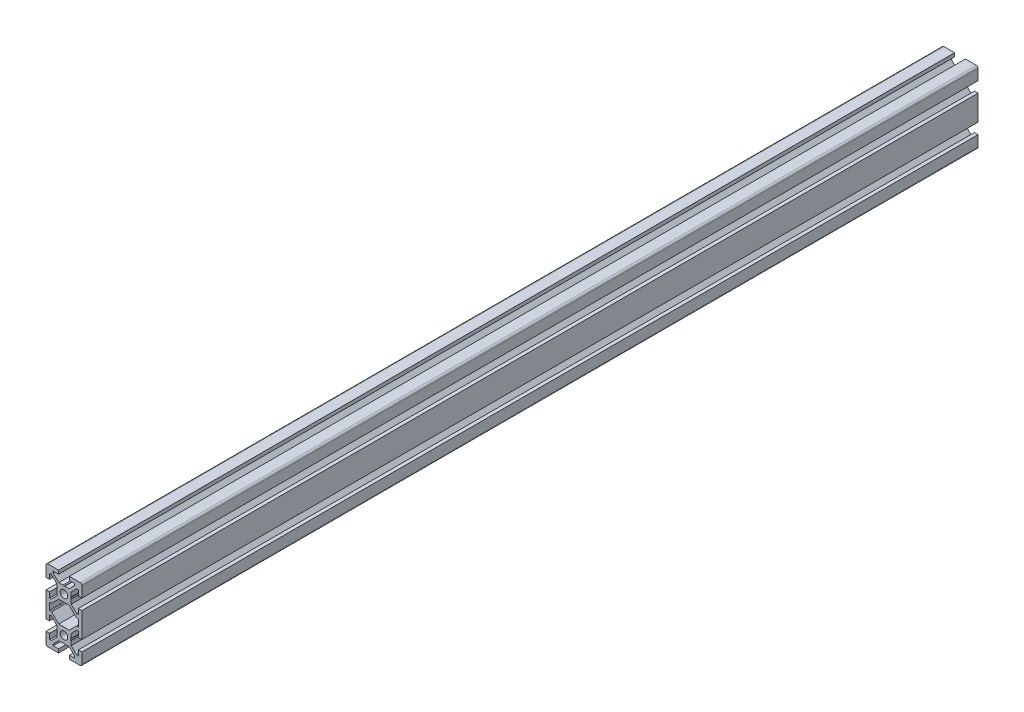
SolidWorks part; units mm, degrees
material "6063-T5"
ref_plane "Front Plane" through (0, 0, 0) normal (0, 0, 1) x (1, 0, 0)
ref_plane "Top Plane" through (0, 0, 0) normal (0, 1, 0) x (1, 0, 0)
ref_plane "Right Plane" through (0, 0, 0) normal (1, 0, 0) x (0, 0, -1)
ref_plane "Plane1" through (0, 0, -50) normal (0, 0, -1) x (-1, 0, 0)
sketch "Sketch1" plane through (0, 0, -50) normal (0, 0, -1) x (-1, 0, 0)
  line L0 (8, 1.7) -> (8, -1.7)
  line L1 (7.7, -2) -> (7.0636, -2)
  line L2 (6.8515, -2.0879) -> (2.9393, -6)
  line L3 (2.9393, -6) -> (-2.9393, -6)
  line L4 (-2.9393, -6) -> (-6.8515, -2.0879)
  line L5 (-7.0636, -2) -> (-7.7, -2)
  line L6 (-8, -1.7) -> (-8, 1.7)
  line L7 (-7.7, 2) -> (-7.0636, 2)
  line L8 (-6.8515, 2.0879) -> (-2.9393, 6)
  line L9 (-2.9393, 6) -> (2.9393, 6)
  line L10 (2.9393, 6) -> (6.8515, 2.0879)
  line L11 (7.0636, 2) -> (7.7, 2)
  line L12 (10, -7) -> (10, 7)
  line L13 (10, 7) -> (8, 7)
  line L14 (8, 7) -> (8, 4)
  line L15 (8, 4) -> (7.0607, 4)
  line L16 (7.0607, 4) -> (4, 7.0607)
  line L17 (4, 7.0607) -> (4, 9.4804)
  line L18 (4, 9.4804) -> (3.7, 10)
  line L19 (3.7, 10) -> (4, 10.5196)
  line L20 (4, 10.5196) -> (4, 12.9393)
  line L21 (4, 12.9393) -> (7.0607, 16)
  line L22 (7.0607, 16) -> (8, 16)
  line L23 (8, 16) -> (8, 13)
  line L24 (8, 13) -> (10, 13)
  line L25 (10, 13) -> (10, 19)
  line L26 (9, 20) -> (3, 20)
  line L27 (3, 20) -> (3, 18)
  line L28 (3, 18) -> (6, 18)
  line L29 (6, 18) -> (6, 17.0607)
  line L30 (6, 17.0607) -> (2.9393, 14)
  line L31 (2.9393, 14) -> (0.5196, 14)
  line L32 (0.5196, 14) -> (0, 13.7)
  line L33 (0, 13.7) -> (-0.5196, 14)
  line L34 (-0.5196, 14) -> (-2.9393, 14)
  line L35 (-2.9393, 14) -> (-6, 17.0607)
  line L36 (-6, 17.0607) -> (-6, 18)
  line L37 (-6, 18) -> (-3, 18)
  line L38 (-3, 18) -> (-3, 20)
  line L39 (-3, 20) -> (-9, 20)
  line L40 (-10, 19) -> (-10, 13)
  line L41 (-10, 13) -> (-8, 13)
  line L42 (-8, 13) -> (-8, 16)
  line L43 (-8, 16) -> (-7.0607, 16)
  line L44 (-7.0607, 16) -> (-4, 12.9393)
  line L45 (-4, 12.9393) -> (-4, 10.5196)
  line L46 (-4, 10.5196) -> (-3.7, 10)
  line L47 (-3.7, 10) -> (-4, 9.4804)
  line L48 (-4, 9.4804) -> (-4, 7.0607)
  line L49 (-4, 7.0607) -> (-7.0607, 4)
  line L50 (-7.0607, 4) -> (-8, 4)
  line L51 (-8, 4) -> (-8, 7)
  line L52 (-8, 7) -> (-10, 7)
  line L53 (-10, 7) -> (-10, -7)
  line L54 (-10, -7) -> (-8, -7)
  line L55 (-8, -7) -> (-8, -4)
  line L56 (-8, -4) -> (-7.0607, -4)
  line L57 (-7.0607, -4) -> (-4, -7.0607)
  line L58 (-4, -7.0607) -> (-4, -9.4804)
  line L59 (-4, -9.4804) -> (-3.7, -10)
  line L60 (-3.7, -10) -> (-4, -10.5196)
  line L61 (-4, -10.5196) -> (-4, -12.9393)
  line L62 (-4, -12.9393) -> (-7.0607, -16)
  line L63 (-7.0607, -16) -> (-8, -16)
  line L64 (-8, -16) -> (-8, -13)
  line L65 (-8, -13) -> (-10, -13)
  line L66 (-10, -13) -> (-10, -19)
  line L67 (-9, -20) -> (-3, -20)
  line L68 (-3, -20) -> (-3, -18)
  line L69 (-3, -18) -> (-6, -18)
  line L70 (-6, -18) -> (-6, -17.0607)
  line L71 (-6, -17.0607) -> (-2.9393, -14)
  line L72 (-2.9393, -14) -> (-0.5196, -14)
  line L73 (-0.5196, -14) -> (0, -13.7)
  line L74 (0, -13.7) -> (0.5196, -14)
  line L75 (0.5196, -14) -> (2.9393, -14)
  line L76 (2.9393, -14) -> (6, -17.0607)
  line L77 (6, -17.0607) -> (6, -18)
  line L78 (6, -18) -> (3, -18)
  line L79 (3, -18) -> (3, -20)
  line L80 (3, -20) -> (9, -20)
  line L81 (10, -19) -> (10, -13)
  line L82 (10, -13) -> (8, -13)
  line L83 (8, -13) -> (8, -16)
  line L84 (8, -16) -> (7.0607, -16)
  line L85 (7.0607, -16) -> (4, -12.9393)
  line L86 (4, -12.9393) -> (4, -10.5196)
  line L87 (4, -10.5196) -> (3.7, -10)
  line L88 (3.7, -10) -> (4, -9.4804)
  line L89 (4, -9.4804) -> (4, -7.0607)
  line L90 (4, -7.0607) -> (7.0607, -4)
  line L91 (7.0607, -4) -> (8, -4)
  line L92 (8, -4) -> (8, -7)
  line L93 (8, -7) -> (10, -7)
  circle A0 centre (0, -10) radius 2.1
  circle A1 centre (0, 10) radius 2.1
  arc A2 (7.7, 2) -> (8, 1.7) centre (7.7, 1.7) cw
  arc A3 (8, -1.7) -> (7.7, -2) centre (7.7, -1.7) cw
  arc A4 (7.0636, -2) -> (6.8515, -2.0879) centre (7.0636, -2.3) ccw
  arc A5 (-6.8515, -2.0879) -> (-7.0636, -2) centre (-7.0636, -2.3) ccw
  arc A6 (-7.7, -2) -> (-8, -1.7) centre (-7.7, -1.7) cw
  arc A7 (-8, 1.7) -> (-7.7, 2) centre (-7.7, 1.7) cw
  arc A8 (-7.0636, 2) -> (-6.8515, 2.0879) centre (-7.0636, 2.3) ccw
  arc A9 (6.8515, 2.0879) -> (7.0636, 2) centre (7.0636, 2.3) ccw
  arc A10 (10, 19) -> (9, 20) centre (9, 19) ccw
  arc A11 (-9, 20) -> (-10, 19) centre (-9, 19) ccw
  arc A12 (-10, -19) -> (-9, -20) centre (-9, -19) ccw
  arc A13 (9, -20) -> (10, -19) centre (9, -19) ccw
extrude "Boss-Extrude1" add sketch "Sketch1" against normal mid plane 499.11
